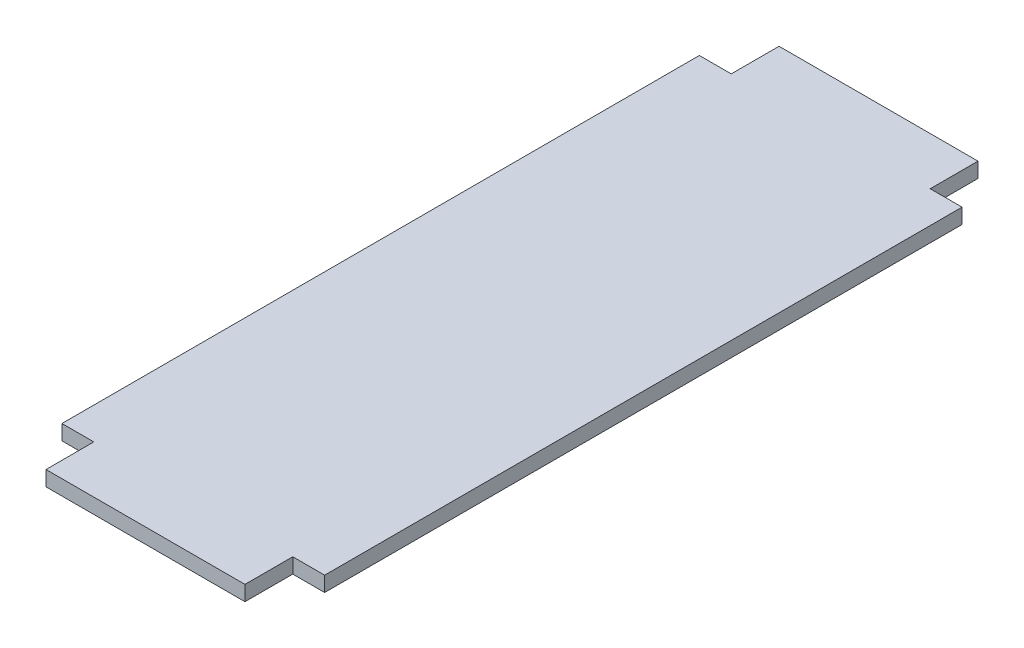
SolidWorks part; units mm, degrees
ref_plane "Front Plane" through (0, 0, 0) normal (0, 0, 1) x (1, 0, 0)
ref_plane "Top Plane" through (0, 0, 0) normal (0, 1, 0) x (1, 0, 0)
ref_plane "Right Plane" through (0, 0, 0) normal (1, 0, 0) x (0, 0, -1)
sketch "Sketch1" plane through (0, 0, 0) normal (0, 1, 0) x (1, 0, 0)
  line L0 (-26.169, 66.4972) -> (26.169, 66.4972) construction
  line L1 (26.169, -73.025) -> (-26.169, -73.025)
  line L2 (26.169, -73.025) -> (26.169, 73.025)
  line L3 (26.169, 73.025) -> (-26.169, 73.025)
  line L4 (-26.169, -73.025) -> (-26.169, 73.025)
  line L5 (26.169, -73.025) -> (-26.169, 73.025) construction
  line L6 (26.169, 73.025) -> (-26.169, -73.025) construction
  line L7 (-26.169, -66.4972) -> (26.169, -66.4972) construction
  line L8 (-26.169, 66.4972) -> (-26.169, -66.4972) construction
  line L9 (26.169, 66.4972) -> (26.169, -66.4972) construction
  line L35 (-26.169, 73.025) -> (-19.819, 73.025)
  line L36 (-26.169, 73.025) -> (-26.169, 63.5)
  line L37 (-26.169, 63.5) -> (-19.819, 63.5)
  line L38 (-19.819, 73.025) -> (-19.819, 63.5)
  line L39 (26.169, 73.025) -> (19.819, 73.025)
  line L40 (26.169, 73.025) -> (26.169, 63.5)
  line L41 (26.169, 63.5) -> (19.819, 63.5)
  line L42 (19.819, 73.025) -> (19.819, 63.5)
  line L43 (-26.169, -73.025) -> (-19.819, -73.025)
  line L44 (-26.169, -73.025) -> (-26.169, -63.5)
  line L45 (-26.169, -63.5) -> (-19.819, -63.5)
  line L46 (-19.819, -73.025) -> (-19.819, -63.5)
  line L47 (26.169, -73.025) -> (19.819, -73.025)
  line L48 (26.169, -73.025) -> (26.169, -63.5)
  line L49 (26.169, -63.5) -> (19.819, -63.5)
  line L50 (19.819, -73.025) -> (19.819, -63.5)
  point P0 (0, 0)
  point P10 (26.169, 0)
  point P11 (26.169, 0)
  point P24 (-11.1666, -58.9268)
  dimension "D1" = 52.338
  dimension "D2" = 146.05
  dimension "D3" = 132.9944
  dimension "D4" = 127
  dimension "D5" = 6.35
extrude "Boss-Extrude1" add sketch "Sketch1" along normal blind 2.9972 contours L1 L50 L49 L2 L41 L42 L3 L38 L37 L4 L45 L46
